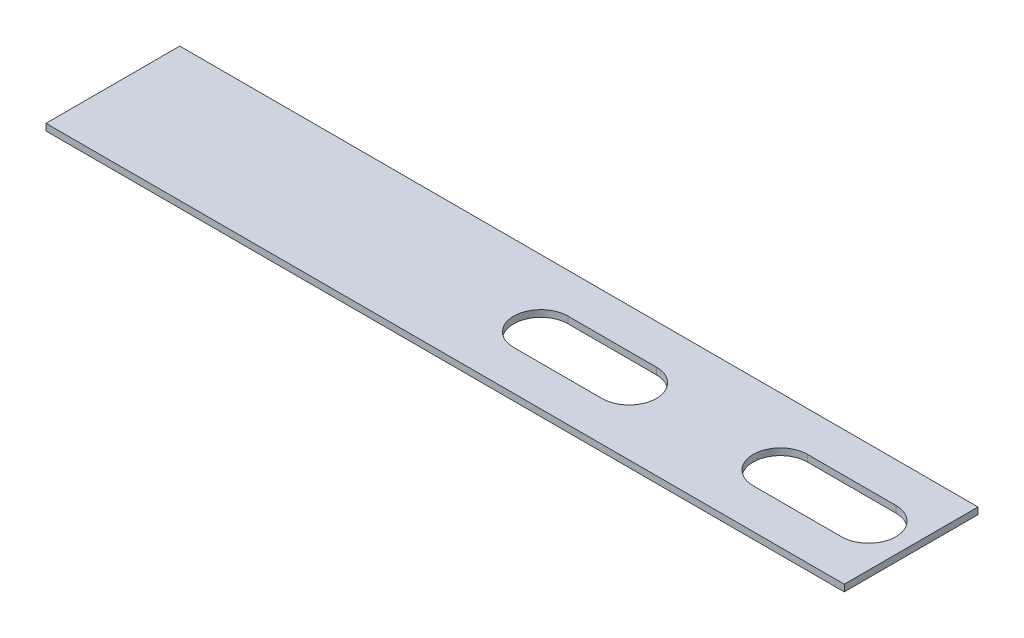
SolidWorks part; units mm, degrees
material "1023 Carbon Steel Sheet (SS)"
ref_plane "Front Plane" through (0, 0, 0) normal (0, 0, 1) x (1, 0, 0)
ref_plane "Top Plane" through (0, 0, 0) normal (0, 1, 0) x (1, 0, 0)
ref_plane "Right Plane" through (0, 0, 0) normal (1, 0, 0) x (0, 0, -1)
sketch "Sketch1" plane through (0, 0, 0) normal (0, 0, 1) x (1, 0, 0)
  line L0 (0, 0) -> (59.69, 0)
  dimension "D1" = 59.69
extrude "Extrude-Thin1" add sketch "Sketch1" along normal blind 10 thin
sketch "Sketch3" plane through (0, 0, 0) normal (0, 1, 0) x (1, 0, 0)
  line L0 (59.69, -5) -> (0, -5) construction
  line L1 (32.004, -5) -> (38.608, -5) construction
  line L2 (32.004, -2.968) -> (38.608, -2.968)
  line L3 (32.004, -7.032) -> (38.608, -7.032)
  line L4 (59.69, 0) -> (0, 0)
  line L5 (0, 0) -> (0, -10)
  line L6 (0, -10) -> (59.69, -10)
  line L7 (59.69, -10) -> (59.69, 0)
  line L8 (59.69, 0) -> (0, 0)
  line L9 (0, 0) -> (0, -10)
  line L10 (0, -10) -> (59.69, -10)
  line L11 (59.69, -10) -> (59.69, 0)
  line L12 (49.911, -5) -> (56.515, -5) construction
  line L13 (49.911, -2.968) -> (56.515, -2.968)
  line L14 (49.911, -7.032) -> (56.515, -7.032)
  arc A0 (32.004, -2.968) -> (32.004, -7.032) centre (32.004, -5) ccw
  arc A1 (38.608, -7.032) -> (38.608, -2.968) centre (38.608, -5) ccw
  arc A2 (49.911, -2.968) -> (49.911, -7.032) centre (49.911, -5) ccw
  arc A3 (56.515, -7.032) -> (56.515, -2.968) centre (56.515, -5) ccw
  point P8 (35.306, -5)
  point P13 (53.213, -5)
  dimension "D2" = 6.604
  dimension "D3" = 4.064
  dimension "D4" = 6.604
  dimension "D5" = 4.064
  dimension "D6" = 3.175
  dimension "D7" = 21.082
  dimension "D1" = 0
extrude "Cut-Extrude5" cut sketch "Sketch3" against normal blind 2.54 flip side to cut
